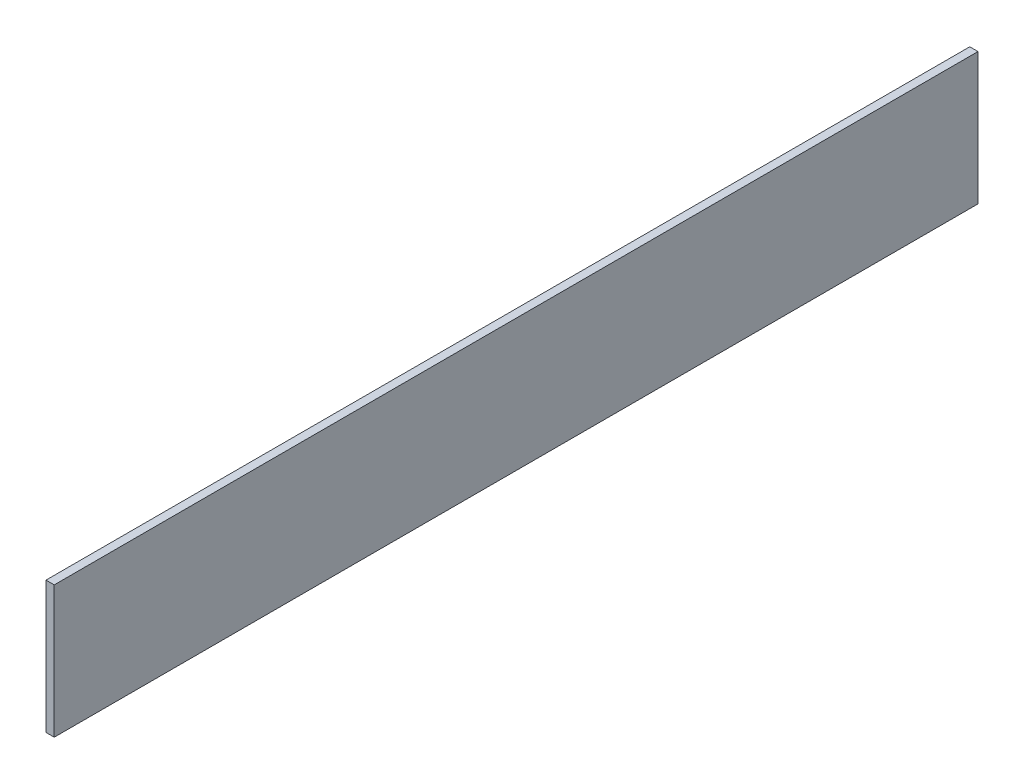
SolidWorks part; units mm, degrees
ref_plane "Front Plane" through (0, 0, 0) normal (0, 0, 1) x (1, 0, 0)
ref_plane "Top Plane" through (0, 0, 0) normal (0, 1, 0) x (1, 0, 0)
ref_plane "Right Plane" through (0, 0, 0) normal (1, 0, 0) x (0, 0, -1)
sketch "Sketch1" plane through (0, 0, 0) normal (1, 0, 0) x (0, 0, -1)
  line L1 (-248.7128, 111.4249) -> (284.6872, 111.4249)
  line L2 (-248.7128, 111.4249) -> (-248.7128, 187.6249)
  line L3 (-248.7128, 187.6249) -> (284.6872, 187.6249)
  line L4 (284.6872, 111.4249) -> (284.6872, 187.6249)
  dimension "D1" = 533.4
  dimension "D2" = 76.2
extrude "Boss-Extrude1" add sketch "Sketch1" along normal blind 4.7625
